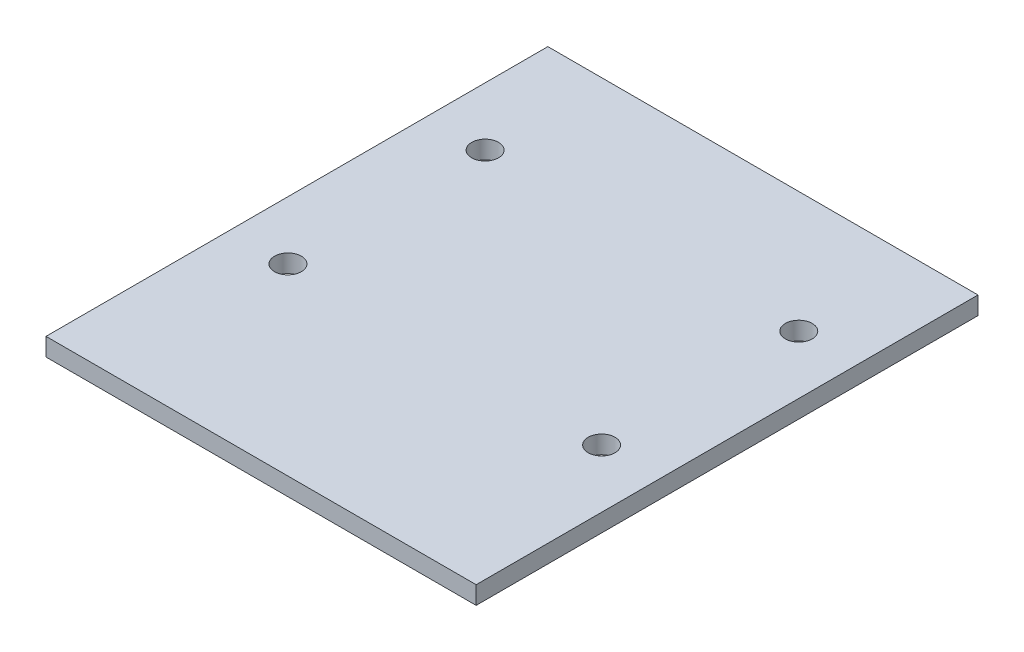
SolidWorks part; units mm, degrees
ref_plane "Front Plane" through (0, 0, 0) normal (0, 0, 1) x (1, 0, 0)
ref_plane "Top Plane" through (0, 0, 0) normal (0, 1, 0) x (1, 0, 0)
ref_plane "Right Plane" through (0, 0, 0) normal (1, 0, 0) x (0, 0, -1)
sketch "Sketch1" plane through (0, 0, 0) normal (0, 1, 0) x (1, 0, 0)
  line L1 (76.2, -88.9) -> (-76.2, -88.9)
  line L2 (76.2, -88.9) -> (76.2, 88.9)
  line L3 (76.2, 88.9) -> (-76.2, 88.9)
  line L4 (-76.2, -88.9) -> (-76.2, 88.9)
  line L5 (76.2, -88.9) -> (-76.2, 88.9) construction
  line L6 (76.2, 88.9) -> (-76.2, -88.9) construction
  point P0 (0, 0)
  dimension "D1" = 177.8
  dimension "D2" = 152.4
extrude "Boss-Extrude1" add sketch "Sketch1" along normal mid plane 6.35
hole_wizard "3/8 (0.375) Diameter Hole1" positions "Sketch2" profile "Sketch3" hole size "3/8" standard "ANSI Inch" end condition through all
sketch "Sketch2" plane through (0, 3.175, 0) normal (0, 1, 0) x (1, 0, 0)
  line L0 (-55.5625, 46.0375) -> (55.5625, 46.0375) construction
  line L1 (55.5625, 46.0375) -> (55.5625, -23.8125) construction
  line L2 (55.5625, -23.8125) -> (-55.5625, -23.8125) construction
  line L4 (-55.5625, 46.0375) -> (-55.5625, -23.8125) construction
  line L6 (0, 0) -> (0, 88.9) construction
  line L7 (76.2, 88.9) -> (-76.2, 88.9) construction
  line L9 (-55.5625, 11.1125) -> (0, 11.1125) construction
  line L11 (0, 11.1125) -> (55.5625, 11.1125) construction
  point P0 (-55.5625, 46.0375)
  point P3 (-55.5625, -23.8125)
  point P6 (55.5625, -23.8125)
  point P9 (55.5625, 46.0375)
  dimension "D1" = 69.85
sketch "Sketch3" plane through (-55.5625, 3.175, -46.0375) normal (1, 0, 0) x (0, 0, 1)
  line L0 (0, 0) -> (0, 6.35)
  line L1 (0, 6.35) -> (4.7625, 6.35)
  line L2 (4.7625, 6.35) -> (4.7625, 0)
  line L5 (4.7625, 0) -> (0, 0)
  line L11 (0, -6.35) -> (0, 107.95) construction
  dimension "Thru Hole Dia." = 9.525
  dimension "Thru Hole Depth" = 6.35
